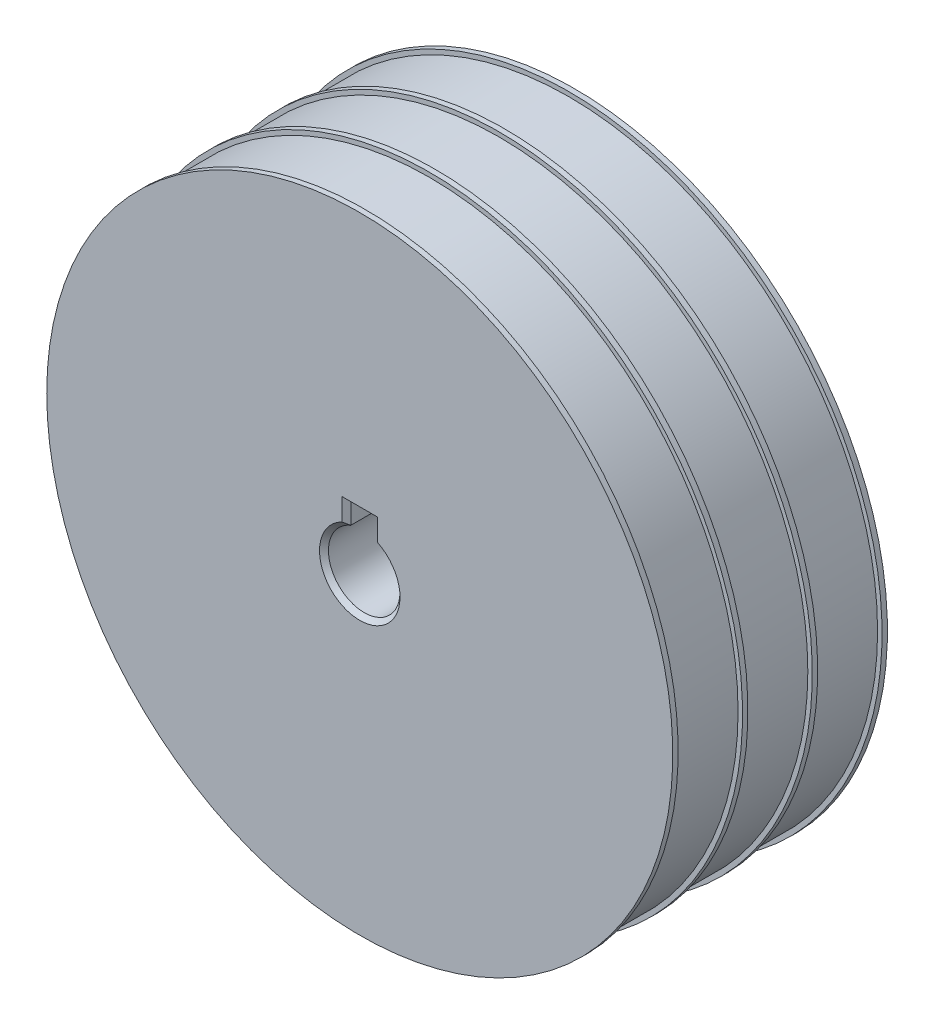
SolidWorks part; units mm, degrees
ref_plane "Front Plane" through (0, 0, 0) normal (0, 0, 1) x (1, 0, 0)
ref_plane "Top Plane" through (0, 0, 0) normal (0, 1, 0) x (1, 0, 0)
ref_plane "Right Plane" through (0, 0, 0) normal (1, 0, 0) x (0, 0, -1)
sketch "Sketch1" plane through (0, 0, 0) normal (0, 1, 0) x (1, 0, 0)
  line L0 (0, 42.5523) -> (0, -40.9466) construction
  line L1 (-4, 25.8905) -> (-35, 25.8905)
  line L2 (-35, 25.8905) -> (-35, 25.2905)
  line L3 (-35, 25.2905) -> (-34.5, 25.2905)
  line L4 (-34.5, 25.2905) -> (-34.5, 18.0905)
  line L5 (-34.5, 18.0905) -> (-35, 18.0905)
  line L7 (-35, 17.4905) -> (-34.5, 17.4905)
  line L8 (-34.5, 17.4905) -> (-34.5, 10.2905)
  line L9 (-34.5, 10.2905) -> (-35, 10.2905)
  line L10 (-35, 10.2905) -> (-35, 9.6905)
  line L11 (-35, 9.6905) -> (-34.5, 9.6905)
  line L12 (-34.5, 9.6905) -> (-34.5, 2.4905)
  line L13 (-34.5, 2.4905) -> (-35, 2.4905)
  line L14 (-35, 2.4905) -> (-35, 1.8905)
  line L15 (-35, 1.8905) -> (-4, 1.8905)
  line L16 (-4, 1.8905) -> (-4, 25.8905)
  line L18 (-35, 18.0905) -> (-35, 17.4905)
  dimension "D1" = 0.6
  dimension "D2" = 4
  dimension "D3" = 0.6
  dimension "D4" = 0.6
  dimension "D5" = 7.2
  dimension "D6" = 7.2
  dimension "D7" = 24
  dimension "D8" = 35
  dimension "D9" = 35
  dimension "D10" = 35
  dimension "D11" = 35
  dimension "D12" = 0.5
  dimension "D13" = 0.5
  dimension "D14" = 0.5
  dimension "D15" = 0.6
  dimension "D16" = 7.2
  dimension "D17" = 0.5
revolve "Revolve1" add sketch "Sketch1" angle 360 about L0
sketch "Sketch2" plane through (0, 0, -25.8905) normal (0, 0, -1) x (-1, 0, 0)
  line L0 (-4, 0) -> (4, 0) construction
  line L1 (-1.5, 0) -> (1.5, 0)
  line L2 (-1.5, 6) -> (1.5, 6)
  line L3 (-1.5, 6) -> (-1.5, 0)
  line L4 (1.5, 6) -> (1.5, 0)
  line L5 (-4, 6) -> (4, 6) construction
  dimension "D1" = 3
  dimension "D2" = 6
extrude "Cut-Extrude1" cut sketch "Sketch2" against normal through all
chamfer "Chamfer1" distance 0.5 angle 45 8 edges at (0, -4, -1.8905) (1.5, 4.854, -1.8905) (0, 6, -1.8905) (-1.5, 4.854, -1.8905) (-1.5, 4.854, -25.8905) (0, 6, -25.8905) (1.5, 4.854, -25.8905) (0, -4, -25.8905)
